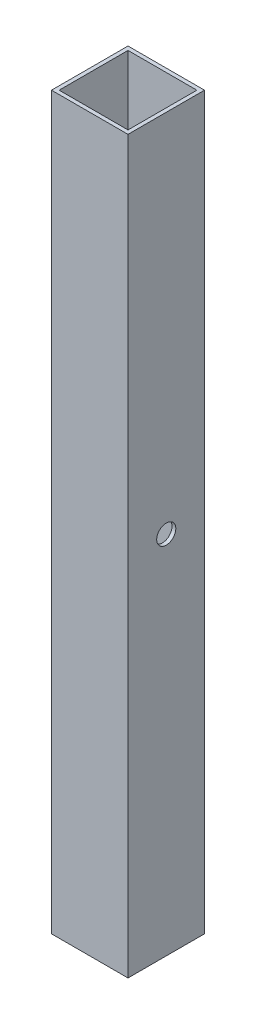
SolidWorks part; units mm, degrees
ref_plane "Front Plane" through (0, 0, 0) normal (0, 0, 1) x (1, 0, 0)
ref_plane "Top Plane" through (0, 0, 0) normal (0, 1, 0) x (1, 0, 0)
ref_plane "Right Plane" through (0, 0, 0) normal (1, 0, 0) x (0, 0, -1)
sketch "Sketch1" plane through (0, 0, 0) normal (0, 1, 0) x (1, 0, 0)
  line L1 (-9, -9) -> (9, -9)
  line L2 (-9, -9) -> (-9, 9)
  line L3 (-9, 9) -> (9, 9)
  line L4 (9, -9) -> (9, 9)
  line L5 (-9, -9) -> (9, 9) construction
  line L6 (-9, 9) -> (9, -9) construction
  line L7 (-10, -10) -> (10, -10)
  line L8 (-10, -10) -> (-10, 10)
  line L9 (-10, 10) -> (10, 10)
  line L10 (10, -10) -> (10, 10)
  line L11 (-10, -10) -> (10, 10) construction
  line L12 (-10, 10) -> (10, -10) construction
  point P0 (0, 0)
  point P6 (0, 0)
  dimension "D1" = 18
  dimension "D2" = 18
  dimension "D3" = 20
  dimension "D4" = 20
extrude "Boss-Extrude1" add sketch "Sketch1" along normal blind 191
sketch "Sketch2" plane through (-10, 0, 0) normal (-1, 0, 0) x (0, 0, 1)
  line L0 (-10, 191) -> (10, 191) construction
  circle A0 centre (0, 95.5) radius 2.5
  dimension "D1" = 5
  dimension "D2" = 95.5
extrude "Cut-Extrude1" cut sketch "Sketch2" against normal through all both and the other way through all
